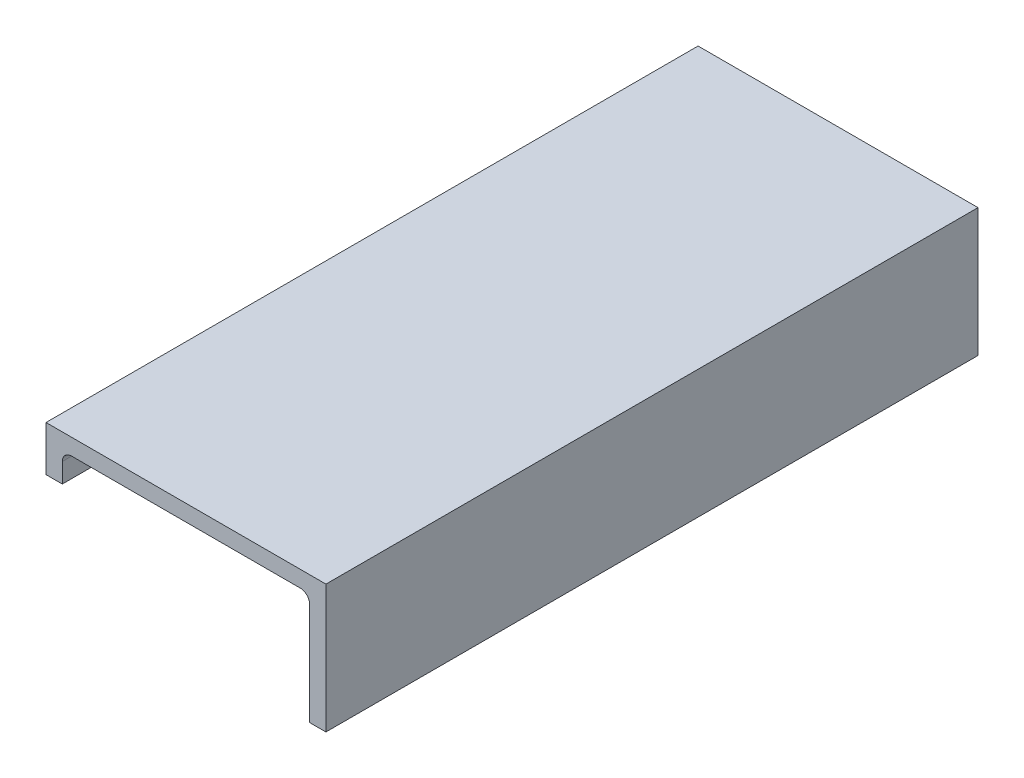
SolidWorks part; units mm, degrees
material "6061 Alloy"
ref_plane "Front Plane" through (0, 0, 0) normal (0, 0, 1) x (1, 0, 0)
ref_plane "Top Plane" through (0, 0, 0) normal (0, 1, 0) x (1, 0, 0)
ref_plane "Right Plane" through (0, 0, 0) normal (1, 0, 0) x (0, 0, -1)
sketch "Sketch1" plane through (0, 0, 0) normal (0, 0, 1) x (1, 0, 0)
  line L0 (0, 0) -> (38.1635, 0)
  line L1 (0, 0) -> (-38.1635, 0)
  line L2 (38.1635, 0) -> (38.1635, -34.925)
  line L3 (-38.1635, 0) -> (-38.1635, -12.319)
  line L4 (-38.1635, -12.319) -> (-33.7185, -12.319)
  line L5 (38.1635, -34.925) -> (33.7185, -34.925)
  line L6 (33.7185, -34.925) -> (33.7185, -4.445)
  line L7 (33.7185, -4.445) -> (-33.7185, -4.445)
  line L8 (-33.7185, -4.445) -> (-33.7185, -12.319)
  dimension "D1" = 38.1635
  dimension "D2" = 38.1635
  dimension "D3" = 34.925
  dimension "D4" = 12.319
  dimension "D5" = 4.445
  dimension "D6" = 4.445
  dimension "D7" = 4.445
extrude "Boss-Extrude1" add sketch "Sketch1" along normal blind 177.8
fillet "Fillet1" radius 2.54 1 edges at (33.7185, -4.445, 88.9)
fillet "Fillet2" radius 2.54 1 edges at (-33.7185, -4.445, 88.9)
